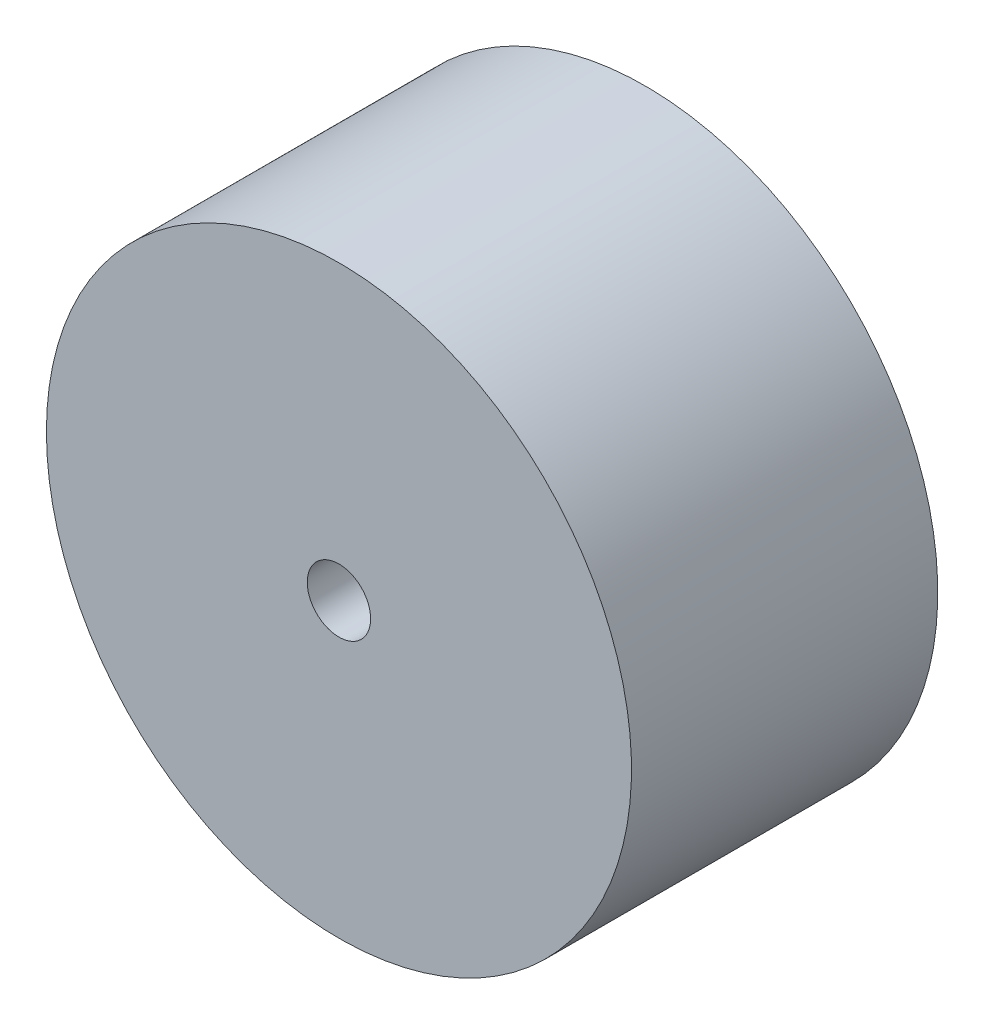
SolidWorks part; units mm, degrees
ref_plane "Front Plane" through (0, 0, 0) normal (0, 0, 1) x (1, 0, 0)
ref_plane "Top Plane" through (0, 0, 0) normal (0, 1, 0) x (1, 0, 0)
ref_plane "Right Plane" through (0, 0, 0) normal (1, 0, 0) x (0, 0, -1)
sketch "Sketch1" plane through (0, 0, 0) normal (0, 0, 1) x (1, 0, 0)
  circle A0 centre (0, 0) radius 13.85
  dimension "D1" = 27.7
extrude "Boss-Extrude1" add sketch "Sketch1" along normal blind 14.5
sketch "Sketch3" plane through (0, 0, 0) normal (0, 0, -1) x (-1, 0, 0)
  circle A0 centre (0, 0) radius 1.5
  dimension "D1" = 3
extrude "Cut-Extrude1" cut sketch "Sketch3" against normal blind 14.5
